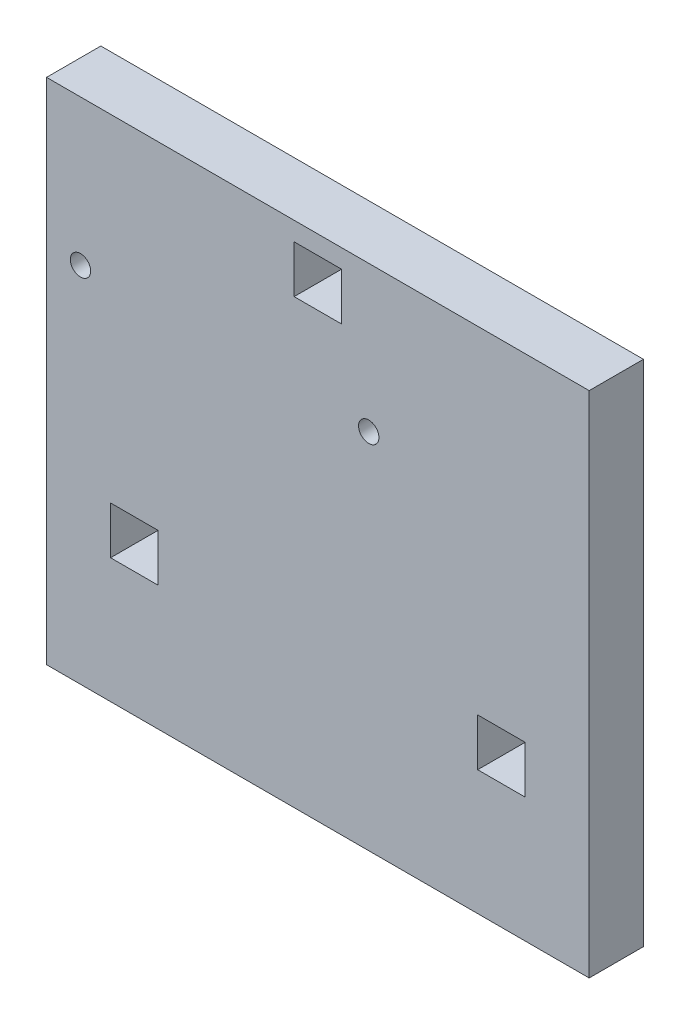
SolidWorks part; units mm, degrees
ref_plane "Front Plane" through (0, 0, 0) normal (0, 0, 1) x (1, 0, 0)
ref_plane "Top Plane" through (0, 0, 0) normal (0, 1, 0) x (1, 0, 0)
ref_plane "Right Plane" through (0, 0, 0) normal (1, 0, 0) x (0, 0, -1)
sketch "Sketch1" plane through (0, 0, 0) normal (0, 0, 1) x (1, 0, 0)
  line L1 (0, 0) -> (-160, 0)
  line L2 (0, 0) -> (0, -150)
  line L3 (0, -150) -> (-160, -150)
  line L4 (-160, 0) -> (-160, -150)
  dimension "D1" = 160
  dimension "D2" = 150
extrude "Boss-Extrude1" add sketch "Sketch1" along normal blind 16
sketch "Sketch2" plane through (0, 0, 16) normal (0, 0, 1) x (1, 0, 0)
  line L0 (-80, 0) -> (-80, -150) construction
  line L1 (0, 0) -> (-160, 0) construction
  line L2 (-160, -150) -> (0, -150) construction
  line L3 (-160, -75) -> (0, -75) construction
  line L4 (-80, -12.5) -> (-134.1266, -106.25) construction
  line L5 (0, -150) -> (0, 0) construction
  line L6 (-160, 0) -> (-160, -150) construction
  line L7 (-80, -12.5) -> (-25.8734, -106.25) construction
  line L8 (-134.1266, -106.25) -> (-25.8734, -106.25) construction
  line L10 (-73, -5.5) -> (-87, -5.5)
  line L11 (-73, -5.5) -> (-73, -19.5)
  line L12 (-73, -19.5) -> (-87, -19.5)
  line L13 (-87, -5.5) -> (-87, -19.5)
  line L14 (-73, -5.5) -> (-87, -19.5) construction
  line L15 (-73, -19.5) -> (-87, -5.5) construction
  line L16 (-127.1266, -113.25) -> (-141.1266, -113.25)
  line L17 (-127.1266, -113.25) -> (-127.1266, -99.25)
  line L18 (-127.1266, -99.25) -> (-141.1266, -99.25)
  line L19 (-141.1266, -113.25) -> (-141.1266, -99.25)
  line L20 (-127.1266, -113.25) -> (-141.1266, -99.25) construction
  line L21 (-127.1266, -99.25) -> (-141.1266, -113.25) construction
  line L22 (-18.8734, -113.25) -> (-32.8734, -113.25)
  line L23 (-18.8734, -113.25) -> (-18.8734, -99.25)
  line L24 (-18.8734, -99.25) -> (-32.8734, -99.25)
  line L25 (-32.8734, -113.25) -> (-32.8734, -99.25)
  line L26 (-18.8734, -113.25) -> (-32.8734, -99.25) construction
  line L27 (-18.8734, -99.25) -> (-32.8734, -113.25) construction
  circle A0 centre (-134.1266, -106.25) radius 7.5 construction
  circle A1 centre (-80, -12.5) radius 7.5 construction
  circle A2 centre (-25.8734, -106.25) radius 7.5 construction
  circle A4 centre (-80, -75) radius 62.5 construction
  dimension "D1" = 15
  dimension "D2" = 125
  dimension "D3" = 14
  dimension "D4" = 14
  dimension "D5" = 14
  dimension "D6" = 14
  dimension "D7" = 14
  dimension "D8" = 14
extrude "Cut-Extrude1" cut sketch "Sketch2" against normal blind 14
sketch "Sketch3" plane through (0, 0, 16) normal (0, 0, 1) x (1, 0, 0)
  line L1 (0, 0) -> (-160, 0) construction
  line L2 (-160, 0) -> (-160, -150) construction
  circle A0 centre (-65, -43) radius 3
  circle A1 centre (-150, -43) radius 3
  dimension "D1" = 6
  dimension "D2" = 6
  dimension "D3" = 10
  dimension "D4" = 95
  dimension "D6" = 43
  dimension "D5" = 43
extrude "Cut-Extrude2" cut sketch "Sketch3" against normal through all
